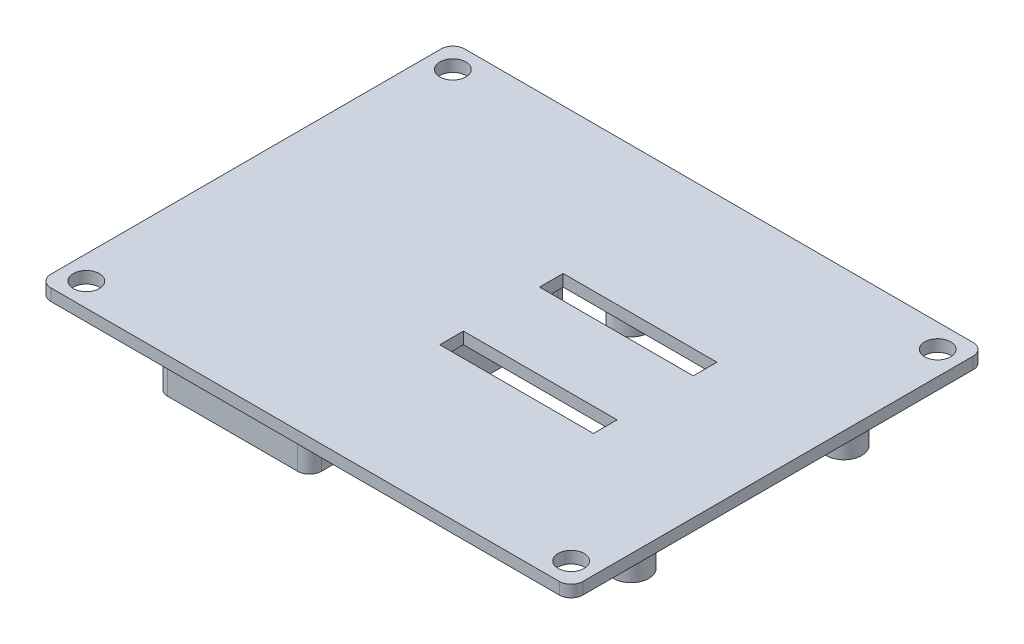
SolidWorks part; units mm, degrees
ref_plane "Front Plane" through (0, 0, 0) normal (0, 0, 1) x (1, 0, 0)
ref_plane "Top Plane" through (0, 0, 0) normal (0, 1, 0) x (1, 0, 0)
ref_plane "Right Plane" through (0, 0, 0) normal (1, 0, 0) x (0, 0, -1)
sketch "Sketch1" plane through (0, 0, 0) normal (0, 1, 0) x (1, 0, 0)
  line L1 (-57.15, -44.45) -> (57.15, -44.45)
  line L2 (-57.15, -44.45) -> (-57.15, 44.45)
  line L3 (-57.15, 44.45) -> (57.15, 44.45)
  line L4 (57.15, -44.45) -> (57.15, 44.45)
  line L5 (-57.15, -44.45) -> (57.15, 44.45) construction
  line L6 (-57.15, 44.45) -> (57.15, -44.45) construction
  point P0 (0, 0)
  dimension "D1" = 88.9
  dimension "D2" = 114.3
extrude "Boss-Extrude2" add sketch "Sketch1" along normal blind 2.54
sketch "Sketch2" plane through (0, 0, 0) normal (0, -1, 0) x (-1, 0, 0)
  line L1 (-52.07, 39.37) -> (52.07, 39.37)
  line L2 (-52.07, 39.37) -> (-52.07, -39.37)
  line L3 (-52.07, -39.37) -> (52.07, -39.37)
  line L4 (52.07, 39.37) -> (52.07, -39.37)
  line L5 (-52.07, 39.37) -> (52.07, -39.37) construction
  line L6 (-52.07, -39.37) -> (52.07, 39.37) construction
  circle A0 centre (52.07, 39.37) radius 2.794
  circle A1 centre (52.07, -39.37) radius 2.794
  circle A2 centre (-52.07, -39.37) radius 2.794
  circle A3 centre (-52.07, 39.37) radius 2.794
  point P0 (0, 0)
  dimension "D3" = 5.588
  dimension "D4" = 5.588
  dimension "D5" = 5.588
  dimension "D6" = 5.588
  dimension "D1" = 104.14
  dimension "D2" = 78.74
extrude "Cut-Extrude1" cut sketch "Sketch2" against normal blind 5.08 contours A0 | A1 | A2 | A3
sketch "Sketch3" plane through (0, 0, 0) normal (0, -1, 0) x (-1, 0, 0)
  line L0 (57.15, 0) -> (-57.15, 0) construction
  line L1 (57.15, 44.45) -> (57.15, -44.45) construction
  line L2 (-57.15, -44.45) -> (-57.15, 44.45) construction
  line L3 (-25.5861, -44.45) -> (-25.5861, 44.45) construction
  line L4 (57.15, -44.45) -> (-57.15, -44.45) construction
  line L5 (-57.15, 44.45) -> (57.15, 44.45) construction
  line L7 (-2.7261, 22.86) -> (-48.4461, 22.86)
  line L8 (-2.7261, 22.86) -> (-2.7261, -22.86)
  line L9 (-2.7261, -22.86) -> (-48.4461, -22.86)
  line L10 (-48.4461, 22.86) -> (-48.4461, -22.86)
  line L11 (-2.7261, 22.86) -> (-48.4461, -22.86) construction
  line L12 (-2.7261, -22.86) -> (-48.4461, 22.86) construction
  circle A0 centre (-2.7261, -22.86) radius 3.81
  circle A1 centre (-48.4461, -22.86) radius 3.81
  circle A2 centre (-48.4461, 22.86) radius 3.81
  circle A3 centre (-2.7261, 22.86) radius 3.81
  circle A4 centre (-48.4461, -22.86) radius 1.651
  circle A5 centre (-2.7261, -22.86) radius 1.651
  circle A6 centre (-48.4461, 22.86) radius 1.651
  circle A7 centre (-2.7261, 22.86) radius 1.651
  point P0 (-25.5861, -0.0292)
  point P13 (-25.5861, 0)
  dimension "D3" = 7.62
  dimension "D4" = 7.62
  dimension "D5" = 7.62
  dimension "D6" = 7.62
  dimension "D7" = 3.302
  dimension "D8" = 3.302
  dimension "D9" = 3.302
  dimension "D10" = 3.302
  dimension "D1" = 45.72
  dimension "D2" = 45.72
sketch "Sketch8" plane through (0, 0, 0) normal (0, -1, 0) x (-1, 0, 0)
  line L1 (48.5659, -27.94) -> (15.5459, -27.94)
  line L2 (48.5659, -27.94) -> (48.5659, 27.94)
  line L3 (48.5659, 27.94) -> (15.5459, 27.94)
  line L4 (15.5459, -27.94) -> (15.5459, 27.94)
  line L5 (48.5659, -27.94) -> (15.5459, 27.94) construction
  line L6 (48.5659, 27.94) -> (15.5459, -27.94) construction
  point P0 (32.0559, 0)
  dimension "D1" = 33.02
  dimension "D2" = 55.88
sketch "Sketch9" plane through (0, 0, 0) normal (0, -1, 0) x (-1, 0, 0)
  line L0 (0, 44.45) -> (0, -44.45) construction
  line L1 (-57.15, 44.45) -> (57.15, 44.45) construction
  line L2 (57.15, -44.45) -> (-57.15, -44.45) construction
  line L3 (-57.15, 0) -> (57.15, 0) construction
  line L4 (-57.15, -44.45) -> (-57.15, 44.45) construction
  line L5 (57.15, 44.45) -> (57.15, -44.45) construction
  line L6 (2.2645, -13.2599) -> (2.2645, -8.1799)
  line L7 (-30.7555, 13.2599) -> (2.2645, 13.2599)
  line L8 (-30.7555, 13.2599) -> (-30.7555, 8.1799)
  line L9 (-30.7555, 8.1799) -> (2.2645, 8.1799)
  line L10 (2.2645, 13.2599) -> (2.2645, 8.1799)
  line L11 (-30.7555, 13.2599) -> (2.2645, 8.1799) construction
  line L12 (-30.7555, 8.1799) -> (2.2645, 13.2599) construction
  line L13 (-30.7555, -8.1799) -> (2.2645, -8.1799)
  line L14 (-30.7555, -13.2599) -> (-30.7555, -8.1799)
  line L15 (-30.7555, -13.2599) -> (2.2645, -13.2599)
  point P12 (-14.2455, 10.7199)
  dimension "D1" = 33.02
  dimension "D2" = 5.08
extrude "Cut-Extrude5" cut sketch "Sketch9" against normal blind 6.35
extrude "Boss-Extrude4" add sketch "Sketch8" along normal blind 21.59 separate body
shell "Shell4" thickness 2.54
sketch "Sketch13" plane through (0, 0, -27.94) normal (0, 0, -1) x (-1, 0, 0)
  line L0 (32.0559, 0) -> (32.0559, -21.59) construction
  line L1 (48.5659, 0) -> (15.5459, 0) construction
  line L2 (48.5659, -21.59) -> (15.5459, -21.59) construction
  line L3 (48.5659, -10.795) -> (15.5459, -10.795) construction
  line L4 (48.5659, -21.59) -> (48.5659, 0) construction
  line L5 (15.5459, -21.59) -> (15.5459, 0) construction
  line L7 (44.3624, -3.7461) -> (19.7495, -3.7461)
  line L8 (44.3624, -3.7461) -> (44.3624, -17.8439)
  line L9 (44.3624, -17.8439) -> (19.7495, -17.8439)
  line L10 (19.7495, -3.7461) -> (19.7495, -17.8439)
  line L11 (44.3624, -3.7461) -> (19.7495, -17.8439) construction
  line L12 (44.3624, -17.8439) -> (19.7495, -3.7461) construction
  point P12 (32.0559, -10.795)
extrude "Cut-Extrude6" cut sketch "Sketch13" against normal blind 5.08
fillet "Fillet5" radius 2.54 1 edges at (-19.7495, -17.8439, -26.67)
fillet "Fillet6" radius 2.54 1 edges at (-19.7495, -3.7461, -26.67)
fillet "Fillet7" radius 2.54 1 edges at (-44.3624, -3.7461, -26.67)
fillet "Fillet8" radius 2.54 1 edges at (-44.3624, -17.8439, -26.67)
fillet "Fillet1" radius 2.54 1 edges at (57.15, 1.27, 44.45)
fillet "Fillet2" radius 2.54 1 edges at (-57.15, 1.27, -44.45)
fillet "Fillet3" radius 2.54 1 edges at (-57.15, 1.27, 44.45)
fillet "Fillet4" radius 2.54 1 edges at (57.15, 1.27, -44.45)
extrude "Boss-Extrude5" add sketch "Sketch3" along normal blind 8.89 contours A3 | A2 | A1 | A0
sketch "Sketch14" plane through (0, -8.89, 0) normal (0, -1, 0) x (1, 0, 0)
  point P0 (48.4461, -22.86)
  point P1 (2.7261, -22.86)
  point P3 (2.7261, 22.86)
  point P5 (48.4461, 22.86)
sketch "Sketch15" plane through (0, -8.89, 0) normal (0, -1, 0) x (-1, 0, 0)
  circle A0 centre (-48.4461, -22.86) radius 1.651
  circle A1 centre (-2.7261, -22.86) radius 1.651
  circle A2 centre (-2.7261, 22.86) radius 1.651
  circle A3 centre (-48.4461, 22.86) radius 1.651
  dimension "D1" = 3.302
  dimension "D2" = 3.302
  dimension "D3" = 3.302
  dimension "D4" = 3.302
extrude "Cut-Extrude7" cut sketch "Sketch15" against normal blind 6.35 draft 2
fillet "Fillet9" radius 2.54 1 edges at (-15.5459, -10.795, -27.94)
fillet "Fillet10" radius 2.54 1 edges at (-15.5459, -10.795, 27.94)
fillet "Fillet11" radius 2.54 1 edges at (-48.5659, -10.795, 27.94)
fillet "Fillet12" radius 2.54 1 edges at (-48.5659, -10.795, -27.94)
